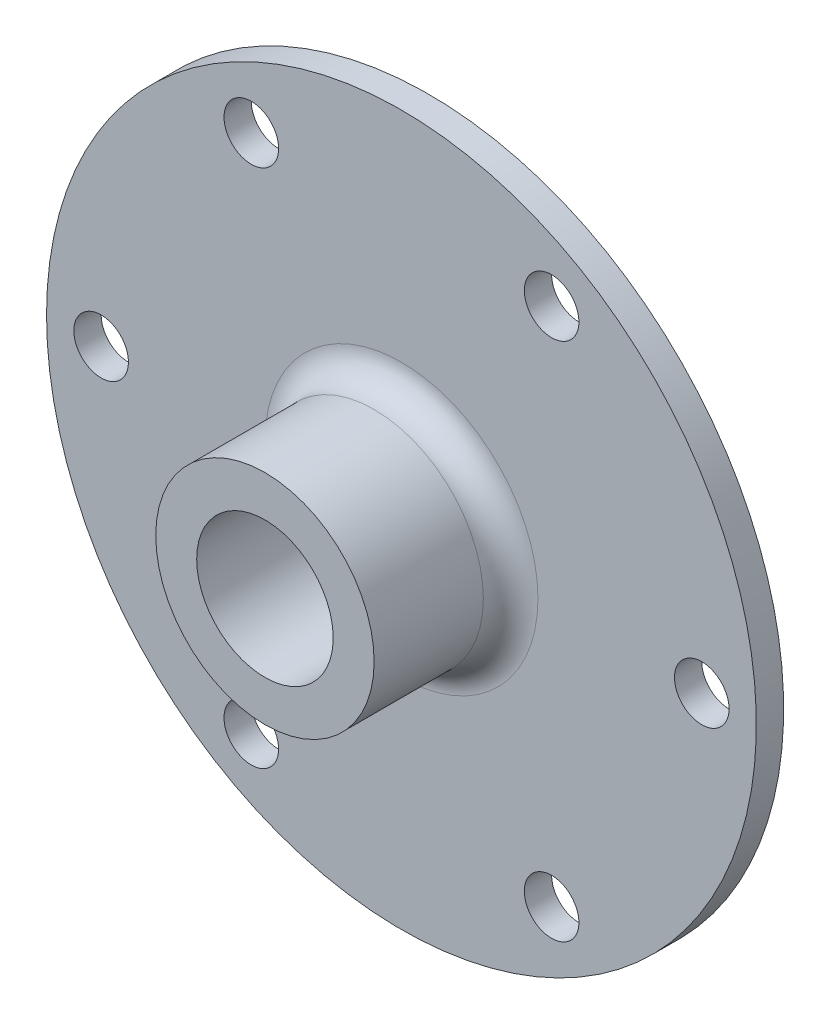
SolidWorks part; units mm, degrees
material "Cast Alloy Steel"
ref_plane "Front Plane" through (0, 0, 0) normal (0, 0, 1) x (1, 0, 0)
ref_plane "Top Plane" through (0, 0, 0) normal (0, 1, 0) x (1, 0, 0)
ref_plane "Right Plane" through (0, 0, 0) normal (1, 0, 0) x (0, 0, -1)
sketch "Sketch1" plane through (0, 0, 0) normal (1, 0, 0) x (0, 0, -1)
  line L0 (0, 7.9375) -> (0, 41.275)
  line L1 (0, 41.275) -> (-3.175, 41.275)
  line L2 (-3.175, 41.275) -> (-3.175, 12.7)
  line L3 (-3.175, 12.7) -> (-19.05, 12.7)
  line L4 (-19.05, 12.7) -> (-19.05, 7.9375)
  line L5 (-19.05, 7.9375) -> (0, 7.9375)
  line L6 (0, 0) -> (-19.05, 0) construction
  dimension "D1" = 19.05
  dimension "D2" = 3.175
  dimension "D3" = 7.9375
  dimension "D4" = 12.7
  dimension "D5" = 41.275
revolve "Revolve1" add sketch "Sketch1" angle 360 about L6
fillet "Fillet1" radius 3.175 1 edges at (-12.7, 0, 3.175)
sketch "Sketch2" plane through (0, 0, 3.175) normal (0, 0, 1) x (1, 0, 0)
  circle A0 centre (0, 0) radius 34.925 construction
  circle A1 centre (34.925, 0) radius 3.175
  dimension "D1" = 69.85
  dimension "D2" = 6.35
extrude "Cut-Extrude1" cut sketch "Sketch2" against normal through all
pattern_circular "CirPattern1" count 6 over 360 about axis through (0, 0, 0) along (0, 0, 1) of "Cut-Extrude1"
scale "Scale1" scale about centroid uniform scaling yes scale factor 0.5
